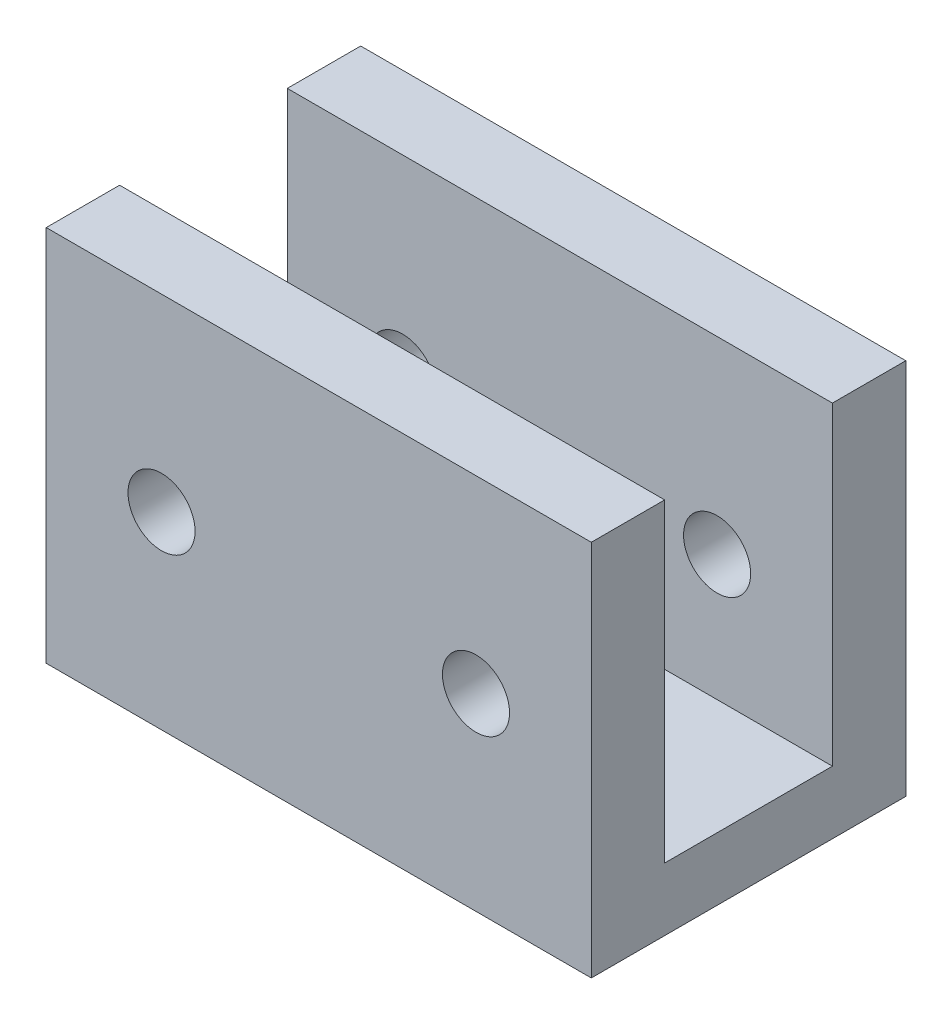
SolidWorks part; units mm, degrees
ref_plane "前视基准面" through (0, 0, 0) normal (0, 0, 1) x (1, 0, 0)
ref_plane "上视基准面" through (0, 0, 0) normal (0, 1, 0) x (1, 0, 0)
ref_plane "右视基准面" through (0, 0, 0) normal (1, 0, 0) x (0, 0, -1)
sketch "草图1" plane through (0, 0, 0) normal (0, 0, 1) x (1, 0, 0)
  line L0 (0, -55) -> (0, 55) construction
  line L2 (-13, -9) -> (13, -9)
  line L3 (-13, -9) -> (-13, 9)
  line L4 (-13, 9) -> (13, 9)
  line L5 (13, -9) -> (13, 9)
  line L6 (-13, -9) -> (13, 9) construction
  line L7 (-13, 9) -> (13, -9) construction
  circle A0 centre (-7.5, 0) radius 1.6
  circle A1 centre (7.5, 0) radius 1.6
  point P6 (0, 0)
  dimension "D1" = 15
  dimension "D2" = 3.2
  dimension "D3" = 18
extrude "凸台-拉伸1" add sketch "草图1" along normal mid plane 15
sketch "草图2" plane through (0, 9, 0) normal (0, 1, 0) x (1, 0, 0)
  line L0 (13, -7.5) -> (13, 7.5) construction
  line L1 (-13, -4) -> (13, -4)
  line L2 (-13, -4) -> (-13, 4)
  line L3 (-13, 4) -> (13, 4)
  line L4 (13, -4) -> (13, 4)
  line L5 (-13, -4) -> (13, 4) construction
  line L6 (-13, 4) -> (13, -4) construction
  point P0 (0, 0)
  dimension "D1" = 8
sketch "草图3" plane through (-13, 0, 0) normal (-1, 0, 0) x (0, 0, 1)
  line L0 (-4, -6) -> (-4, 9)
  line L1 (-4, -6) -> (4, -6)
  line L2 (-4, 9) -> (4, 9)
  line L3 (4, -6) -> (4, 9)
  line L4 (-4, -6) -> (4, 9) construction
  line L5 (-4, 9) -> (4, -6) construction
  line L6 (7.5, -9) -> (-7.5, -9) construction
  line L7 (4, 9) -> (-4, 9) construction
  point P1 (0, 1.5)
  dimension "D1" = 3
  dimension "D2" = 8
extrude "切除-拉伸2" cut sketch "草图3" against normal blind 30
